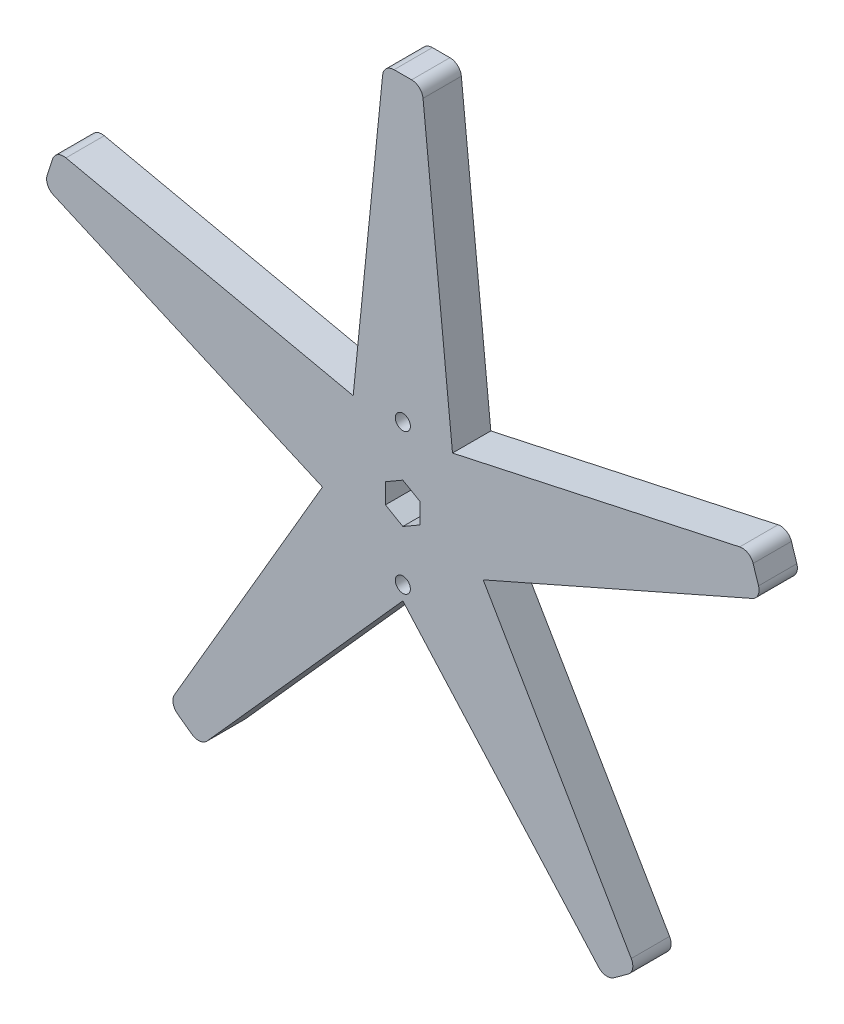
SolidWorks part; units mm, degrees
ref_plane "Front Plane" through (0, 0, 0) normal (0, 0, 1) x (1, 0, 0)
ref_plane "Top Plane" through (0, 0, 0) normal (0, 1, 0) x (1, 0, 0)
ref_plane "Right Plane" through (0, 0, 0) normal (1, 0, 0) x (0, 0, -1)
sketch "Sketch1" plane through (0, 0, 0) normal (0, 0, 1) x (1, 0, 0)
  line L0 (0, 41.9404) -> (0, 204.0596) construction
  line L1 (0, 41.9404) -> (0, 4.742) construction
  line L2 (0, 0) -> (0, 4.742) construction
  line L3 (0, 4.742) -> (0, 0) construction
  line L5 (0, -6.65) -> (5.7591, -3.325)
  line L6 (5.7591, -3.325) -> (5.7591, 3.325)
  line L7 (0, 204.0596) -> (0, 41.9404) construction
  line L8 (-2.9045, 123) -> (2.9045, 123)
  line L9 (-6.6953, 119.5718) -> (-16.458, 22.6525)
  line L10 (6.6953, 119.5718) -> (16.458, 22.6525)
  line L11 (-16.458, 22.6525) -> (0, 0) construction
  line L12 (0, 0) -> (16.458, 22.6525) construction
  line L13 (111.6506, 43.3174) -> (16.458, 22.6525)
  line L14 (116.0824, 40.7714) -> (117.8775, 35.2467)
  line L15 (115.7886, 30.5821) -> (26.6296, -8.6525)
  line L16 (75.6992, -92.8002) -> (26.6296, -8.6525)
  line L17 (74.6474, -97.8019) -> (69.9478, -101.2163)
  line L18 (64.8659, -100.6711) -> (0, -28)
  line L19 (-64.8659, -100.6711) -> (0, -28)
  line L20 (-69.9478, -101.2163) -> (-74.6474, -97.8019)
  line L21 (-75.6992, -92.8002) -> (-26.6296, -8.6525)
  line L22 (-115.7886, 30.5821) -> (-26.6296, -8.6525)
  line L23 (-117.8775, 35.2467) -> (-116.0824, 40.7714)
  line L24 (-111.6506, 43.3174) -> (-16.458, 22.6525)
  line L25 (5.7591, 3.325) -> (0, 6.65)
  line L26 (0, 6.65) -> (-5.7591, 3.325)
  line L27 (-5.7591, 3.325) -> (-5.7591, -3.325)
  line L28 (-5.7591, -3.325) -> (0, -6.65)
  circle A0 centre (0, 0) radius 28 construction
  arc A1 (6.6953, 119.5718) -> (2.9045, 123) centre (2.9045, 119.19) ccw
  arc A2 (-6.6953, 119.5718) -> (-2.9045, 123) centre (-2.9045, 119.19) cw
  arc A3 (111.6506, 43.3174) -> (116.0824, 40.7714) centre (112.4589, 39.5941) cw
  arc A4 (115.7886, 30.5821) -> (117.8775, 35.2467) centre (114.254, 34.0694) ccw
  arc A5 (75.6992, -92.8002) -> (74.6474, -97.8019) centre (72.4079, -94.7195) cw
  arc A6 (64.8659, -100.6711) -> (69.9478, -101.2163) centre (67.7083, -98.134) ccw
  arc A7 (-64.8659, -100.6711) -> (-69.9478, -101.2163) centre (-67.7083, -98.134) cw
  arc A8 (-75.6992, -92.8002) -> (-74.6474, -97.8019) centre (-72.4079, -94.7195) ccw
  arc A9 (-115.7886, 30.5821) -> (-117.8775, 35.2467) centre (-114.254, 34.0694) cw
  arc A10 (-111.6506, 43.3174) -> (-116.0824, 40.7714) centre (-112.4589, 39.5941) ccw
  circle A11 centre (0, 0) radius 5.7591 construction
  circle A12 centre (0, 23.3412) radius 2.5
  circle A13 centre (0, -23.3412) radius 2.5
  point P11 (0, 123)
  point P16 (6.35, 123)
  point P19 (-6.35, 123)
  point P20 (0, 28)
  point P35 (0, 0)
  point P58 (0, 0)
  dimension "D1" = 13.3
  dimension "D6" = 3.81
  dimension "D2" = 5
  dimension "D9" = 56
  dimension "D4" = 95
  dimension "D3" = 2
  dimension "D5" = 72
  dimension "D7" = 12.7
  dimension "D10" = 23.3412
  dimension "D8" = 5
extrude "Boss-Extrude1" add sketch "Sketch1" along normal blind 12.7
sketch "Sketch2" plane through (0, 0, 12.7) normal (0, 0, 1) x (1, 0, 0)
  circle A0 centre (0, 0) radius 28
  dimension "D1" = 56
sketch "Sketch3" plane through (0, 0, 0) normal (0, 0, -1) x (-1, 0, 0)
  circle A0 centre (0, 0) radius 28
  dimension "D1" = 56
